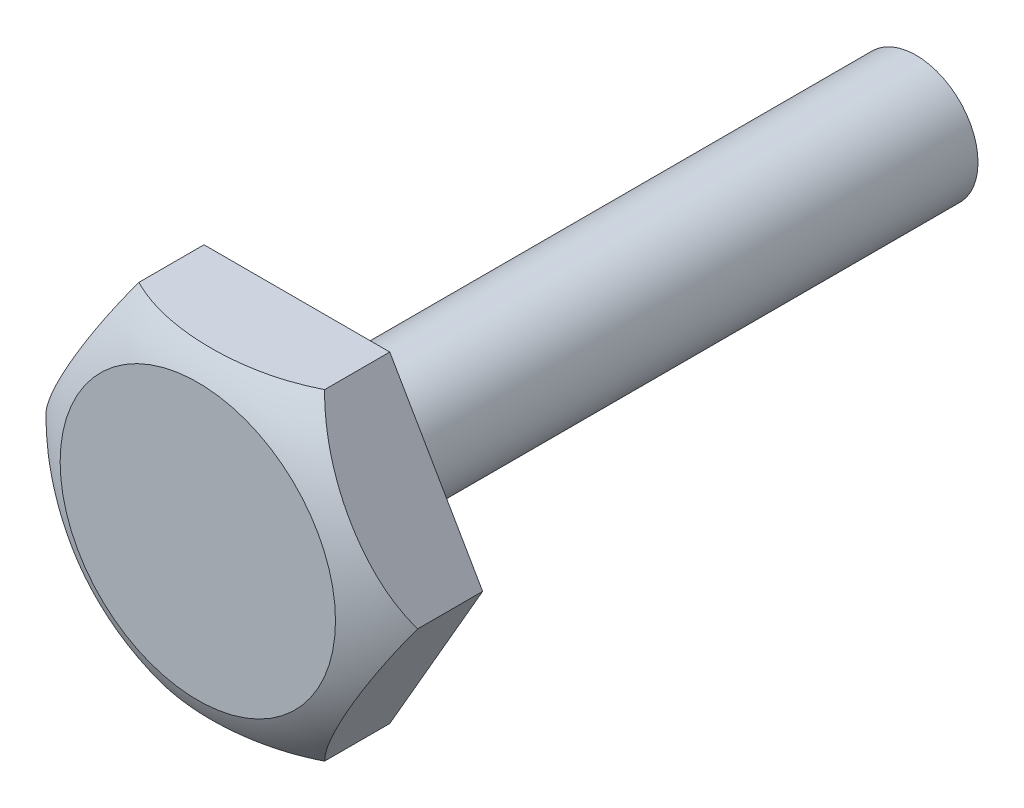
SolidWorks part; units mm, degrees
ref_plane "Front Plane" through (0, 0, 0) normal (0, 0, 1) x (1, 0, 0)
ref_plane "Top Plane" through (0, 0, 0) normal (0, 1, 0) x (1, 0, 0)
ref_plane "Right Plane" through (0, 0, 0) normal (1, 0, 0) x (0, 0, -1)
sketch "Sketch1" plane through (0, 0, 0) normal (0, 0, 1) x (1, 0, 0)
  line L1 (7.5, 0) -> (3.75, 6.4952)
  line L2 (3.75, 6.4952) -> (-3.75, 6.4952)
  line L3 (-3.75, 6.4952) -> (-7.5, 0)
  line L4 (-7.5, 0) -> (-3.75, -6.4952)
  line L5 (-3.75, -6.4952) -> (3.75, -6.4952)
  line L6 (3.75, -6.4952) -> (7.5, 0)
  circle A0 centre (0, 0) radius 7.5 construction
  circle A1 centre (0, 0) radius 6.4952 construction
extrude "Boss-Extrude1" add sketch "Sketch1" along normal blind 4
sketch "Sketch2" plane through (0, 0, 0) normal (0, 0, 1) x (1, 0, 0)
  circle A0 centre (0, 0) radius 2.5
extrude "Boss-Extrude2" add sketch "Sketch2" against normal blind 25
sketch "Sketch4" plane through (0, 0, 0) normal (1, 0, 0) x (0, 0, -1)
  line L0 (-1.7226, 8.2366) -> (-4.5183, 8.2366)
  line L3 (-4.5183, 8.2366) -> (-4.5183, 5.3925)
  line L4 (-4.5183, 5.3925) -> (-4.0736, 5.3925)
  line L5 (0, 0) -> (-2.8397, 0) construction
  arc A0 (-4.0736, 5.3925) -> (-1.7226, 8.2366) centre (1.9053, 2.844) cw
revolve "Cut-Revolve1" cut sketch "Sketch4" angle 360 about L5
